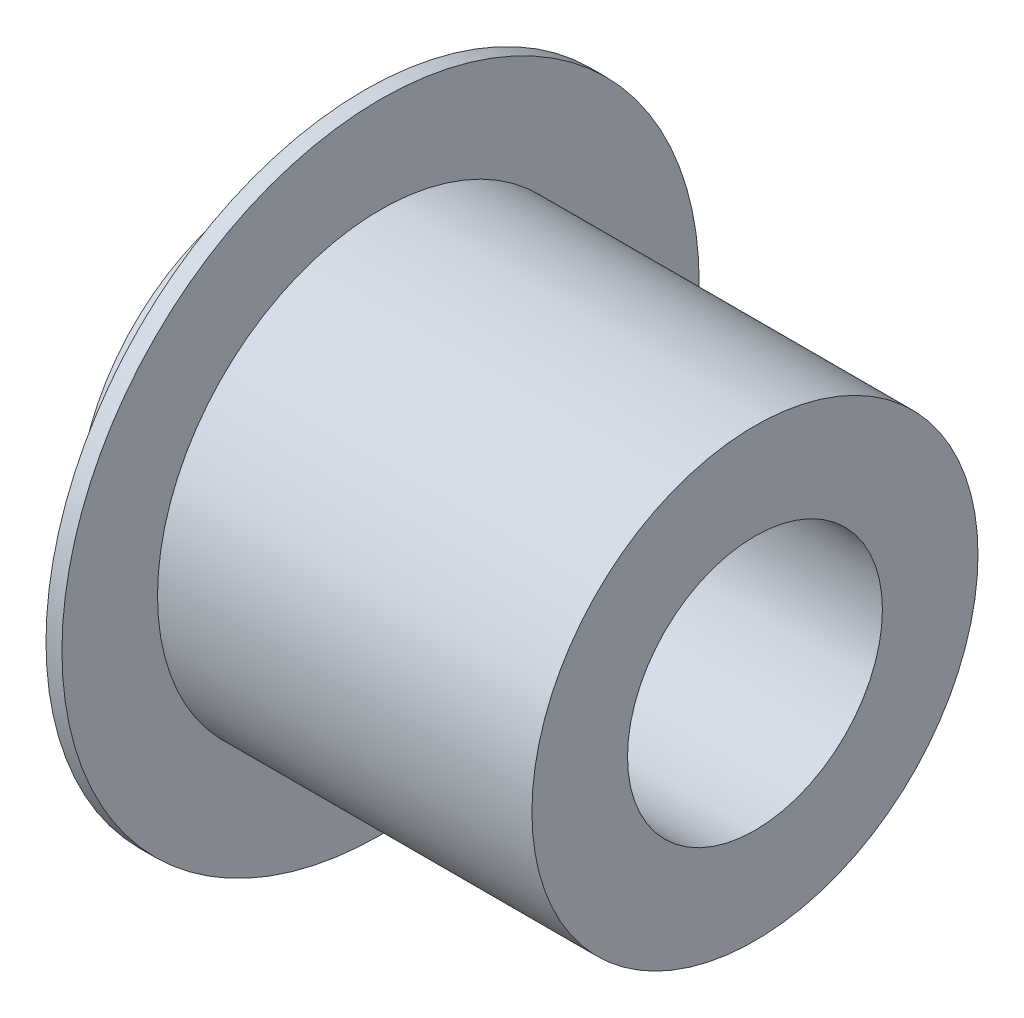
SolidWorks part; units mm, degrees
ref_plane "前视基准面" through (0, 0, 0) normal (0, 0, 1) x (1, 0, 0)
ref_plane "上视基准面" through (0, 0, 0) normal (0, 1, 0) x (1, 0, 0)
ref_plane "右视基准面" through (0, 0, 0) normal (1, 0, 0) x (0, 0, -1)
sketch "草图1" plane through (0, 0, 0) normal (0, 0, 1) x (1, 0, 0)
  line L0 (-25.3713, 0) -> (28.7189, 0) construction
  line L1 (0, 8) -> (0, 12)
  line L2 (0, 12) -> (1, 12)
  line L3 (1, 12) -> (3, 14)
  line L4 (3, 14) -> (6, 14)
  line L5 (6, 14) -> (6, 20)
  line L6 (6, 20) -> (7, 20)
  line L7 (7, 20) -> (7, 14)
  line L8 (7, 14) -> (30.5, 14)
  line L9 (30.5, 14) -> (30.5, 8)
  line L10 (0, 8) -> (30.5, 8)
  dimension "D1" = 45
  dimension "D2" = 23.5
  dimension "D3" = 8
  dimension "D4" = 1
  dimension "D5" = 1
  dimension "D6" = 30.5
  dimension "D7" = 14
  dimension "D8" = 14
  dimension "D9" = 20
  dimension "D10" = 12
revolve "旋转1" add sketch "草图1" angle 360 about L0
